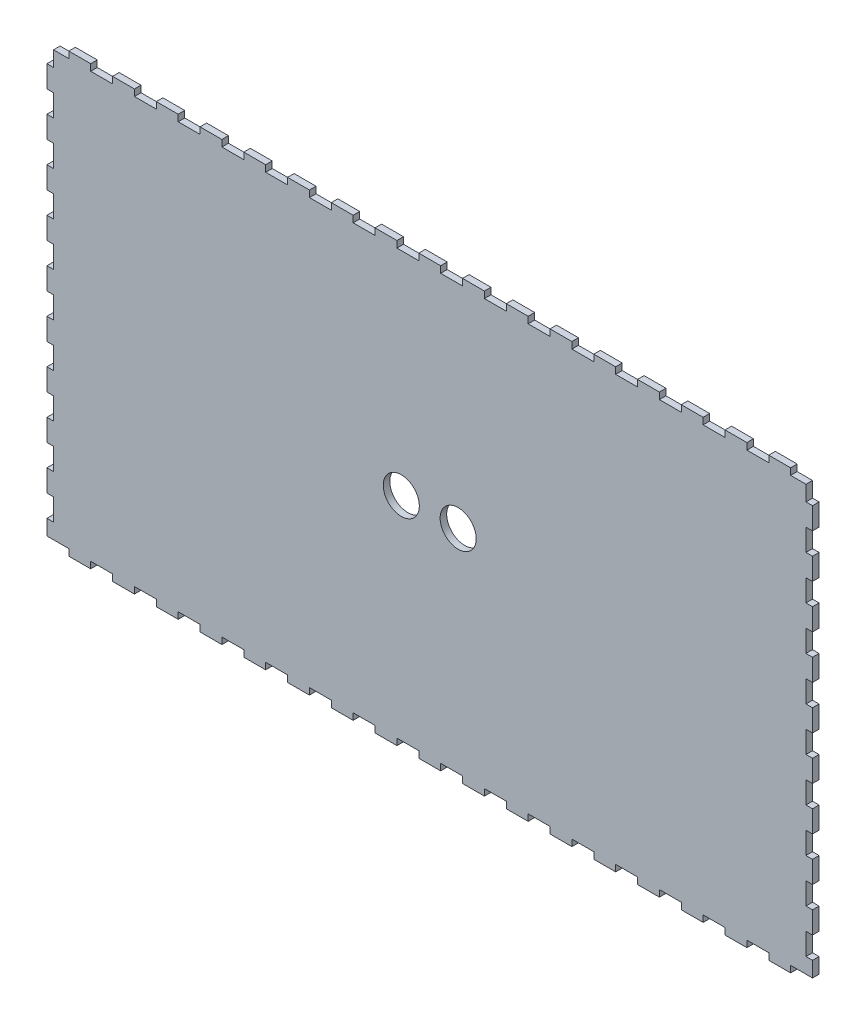
SolidWorks part; units mm, degrees
ref_plane "Alzado" through (0, 0, 0) normal (0, 0, 1) x (1, 0, 0)
ref_plane "Planta" through (0, 0, 0) normal (0, 1, 0) x (1, 0, 0)
ref_plane "Vista lateral" through (0, 0, 0) normal (1, 0, 0) x (0, 0, -1)
sketch "Croquis1" plane through (0, 0, 0) normal (0, 0, 1) x (1, 0, 0)
  line L0 (-175, -97) -> (-165, -97)
  line L1 (-155, -97) -> (-145, -97)
  line L3 (-175, 80) -> (-172, 80)
  line L4 (-172, 70) -> (-175, 70)
  line L5 (175, -100) -> (-175, 100) construction
  line L6 (175, 100) -> (-175, -100) construction
  line L103 (172, 97) -> (172, 90)
  line L105 (-172, 90) -> (-175, 90)
  line L106 (-175, 90) -> (-175, 80)
  line L107 (-175, 80) -> (-172, 80)
  line L108 (-175, 70) -> (-175, 60)
  line L109 (-175, 60) -> (-172, 60)
  line L110 (-172, 80) -> (-172, 70)
  line L111 (-175, 60) -> (-172, 60)
  line L112 (-172, 50) -> (-175, 50)
  line L113 (-175, 50) -> (-175, 40)
  line L114 (-175, 40) -> (-172, 40)
  line L115 (-172, 60) -> (-172, 50)
  line L116 (-175, 40) -> (-172, 40)
  line L117 (-172, 30) -> (-175, 30)
  line L118 (-175, 30) -> (-175, 20)
  line L119 (-175, 20) -> (-172, 20)
  line L120 (-172, 40) -> (-172, 30)
  line L121 (-175, 20) -> (-172, 20)
  line L122 (-172, 10) -> (-175, 10)
  line L123 (-175, 10) -> (-175, 0)
  line L124 (-175, 0) -> (-172, 0)
  line L125 (-172, 20) -> (-172, 10)
  line L126 (-175, 0) -> (-172, 0)
  line L127 (-172, -10) -> (-175, -10)
  line L128 (-175, -10) -> (-175, -20)
  line L129 (-175, -20) -> (-172, -20)
  line L130 (-172, 0) -> (-172, -10)
  line L131 (-175, -20) -> (-172, -20)
  line L132 (-172, -30) -> (-175, -30)
  line L133 (-175, -30) -> (-175, -40)
  line L134 (-175, -40) -> (-172, -40)
  line L135 (-172, -20) -> (-172, -30)
  line L136 (-175, -40) -> (-172, -40)
  line L137 (-172, -50) -> (-175, -50)
  line L138 (-175, -50) -> (-175, -60)
  line L139 (-175, -60) -> (-172, -60)
  line L140 (-172, -40) -> (-172, -50)
  line L141 (-175, -60) -> (-172, -60)
  line L142 (-172, -70) -> (-175, -70)
  line L143 (-175, -70) -> (-175, -80)
  line L144 (-175, -80) -> (-172, -80)
  line L145 (-172, -60) -> (-172, -70)
  line L146 (-175, -80) -> (-172, -80)
  line L147 (-172, -90) -> (-175, -90)
  line L148 (-175, -90) -> (-175, -97)
  line L149 (-145, -97) -> (-145, -100)
  line L150 (-172, -80) -> (-172, -90)
  line L151 (-33.9734, 0) -> (38.9566, 0) construction
  line L152 (172, -80) -> (172, -90)
  line L153 (165, 97) -> (172, 97)
  line L154 (175, -90) -> (175, -97)
  line L155 (172, -90) -> (175, -90)
  line L156 (175, -80) -> (172, -80)
  line L157 (172, -60) -> (172, -70)
  line L158 (175, -80) -> (172, -80)
  line L159 (175, -70) -> (175, -80)
  line L160 (172, -70) -> (175, -70)
  line L161 (175, -60) -> (172, -60)
  line L162 (172, -40) -> (172, -50)
  line L163 (175, -60) -> (172, -60)
  line L164 (175, -50) -> (175, -60)
  line L165 (172, -50) -> (175, -50)
  line L166 (175, -40) -> (172, -40)
  line L167 (172, -20) -> (172, -30)
  line L168 (175, -40) -> (172, -40)
  line L169 (175, -30) -> (175, -40)
  line L170 (172, -30) -> (175, -30)
  line L171 (175, -20) -> (172, -20)
  line L172 (172, 0) -> (172, -10)
  line L173 (175, -20) -> (172, -20)
  line L174 (175, -10) -> (175, -20)
  line L175 (172, -10) -> (175, -10)
  line L176 (175, 0) -> (172, 0)
  line L177 (172, 20) -> (172, 10)
  line L178 (175, 0) -> (172, 0)
  line L179 (175, 10) -> (175, 0)
  line L180 (172, 10) -> (175, 10)
  line L181 (175, 20) -> (172, 20)
  line L182 (172, 40) -> (172, 30)
  line L183 (175, 20) -> (172, 20)
  line L184 (175, 30) -> (175, 20)
  line L186 (172, 30) -> (175, 30)
  line L187 (175, 40) -> (172, 40)
  line L188 (172, 60) -> (172, 50)
  line L189 (175, 40) -> (172, 40)
  line L190 (175, 50) -> (175, 40)
  line L191 (172, 50) -> (175, 50)
  line L192 (175, 60) -> (172, 60)
  line L193 (172, 80) -> (172, 70)
  line L194 (175, 60) -> (172, 60)
  line L195 (175, 70) -> (175, 60)
  line L196 (175, 80) -> (172, 80)
  line L197 (175, 90) -> (175, 80)
  line L198 (172, 90) -> (175, 90)
  line L200 (172, 70) -> (175, 70)
  line L201 (175, 80) -> (172, 80)
  line L203 (-165, -97) -> (-165, -100)
  line L204 (-165, -100) -> (-155, -100)
  line L205 (-155, -100) -> (-155, -97)
  line L206 (-145, -100) -> (-135, -100)
  line L207 (-135, -100) -> (-135, -97)
  line L208 (-135, -97) -> (-125, -97)
  line L209 (-125, -97) -> (-125, -100)
  line L210 (-125, -100) -> (-115, -100)
  line L211 (-115, -100) -> (-115, -97)
  line L212 (-115, -97) -> (-105, -97)
  line L213 (-105, -97) -> (-105, -100)
  line L214 (-105, -100) -> (-95, -100)
  line L215 (-95, -100) -> (-95, -97)
  line L216 (-95, -97) -> (-85, -97)
  line L217 (-85, -97) -> (-85, -100)
  line L218 (-85, -100) -> (-75, -100)
  line L219 (-75, -100) -> (-75, -97)
  line L220 (-75, -97) -> (-65, -97)
  line L221 (-65, -97) -> (-65, -100)
  line L222 (-65, -100) -> (-55, -100)
  line L223 (-55, -100) -> (-55, -97)
  line L224 (-55, -97) -> (-45, -97)
  line L225 (-45, -97) -> (-45, -100)
  line L226 (-45, -100) -> (-35, -100)
  line L227 (-35, -100) -> (-35, -97)
  line L228 (-35, -97) -> (-25, -97)
  line L229 (-25, -97) -> (-25, -100)
  line L230 (-25, -100) -> (-15, -100)
  line L231 (-15, -100) -> (-15, -97)
  line L232 (-15, -97) -> (-5, -97)
  line L233 (-5, -97) -> (-5, -100)
  line L234 (-5, -100) -> (5, -100)
  line L235 (5, -100) -> (5, -97)
  line L236 (5, -97) -> (15, -97)
  line L237 (15, -97) -> (15, -100)
  line L238 (15, -100) -> (25, -100)
  line L239 (25, -100) -> (25, -97)
  line L240 (25, -97) -> (35, -97)
  line L241 (35, -97) -> (35, -100)
  line L242 (35, -100) -> (45, -100)
  line L243 (45, -100) -> (45, -97)
  line L244 (45, -97) -> (55, -97)
  line L245 (55, -97) -> (55, -100)
  line L246 (55, -100) -> (65, -100)
  line L247 (65, -100) -> (65, -97)
  line L248 (65, -97) -> (75, -97)
  line L249 (75, -97) -> (75, -100)
  line L250 (75, -100) -> (85, -100)
  line L251 (85, -100) -> (85, -97)
  line L255 (85, -97) -> (95, -97)
  line L256 (95, -97) -> (95, -100)
  line L257 (95, -100) -> (105, -100)
  line L258 (105, -100) -> (105, -97)
  line L259 (105, -97) -> (115, -97)
  line L260 (115, -97) -> (115, -100)
  line L261 (115, -100) -> (125, -100)
  line L262 (125, -100) -> (125, -97)
  line L263 (125, -97) -> (135, -97)
  line L264 (135, -97) -> (135, -100)
  line L265 (135, -100) -> (145, -100)
  line L266 (145, -100) -> (145, -97)
  line L267 (145, -97) -> (155, -97)
  line L268 (155, -97) -> (155, -100)
  line L269 (155, -100) -> (165, -100)
  line L270 (165, -100) -> (165, -97)
  line L271 (165, -97) -> (175, -97)
  line L272 (165, 100) -> (165, 97)
  line L273 (155, 100) -> (165, 100)
  line L274 (155, 97) -> (155, 100)
  line L275 (145, 97) -> (155, 97)
  line L276 (145, 100) -> (145, 97)
  line L277 (135, 100) -> (145, 100)
  line L278 (135, 97) -> (135, 100)
  line L279 (125, 97) -> (135, 97)
  line L280 (125, 100) -> (125, 97)
  line L281 (115, 100) -> (125, 100)
  line L282 (115, 97) -> (115, 100)
  line L283 (105, 97) -> (115, 97)
  line L284 (105, 100) -> (105, 97)
  line L285 (95, 100) -> (105, 100)
  line L286 (95, 97) -> (95, 100)
  line L287 (85, 97) -> (95, 97)
  line L288 (85, 100) -> (85, 97)
  line L289 (75, 100) -> (85, 100)
  line L290 (75, 97) -> (75, 100)
  line L291 (65, 97) -> (75, 97)
  line L292 (65, 100) -> (65, 97)
  line L293 (55, 100) -> (65, 100)
  line L294 (55, 97) -> (55, 100)
  line L295 (45, 97) -> (55, 97)
  line L296 (45, 100) -> (45, 97)
  line L297 (35, 100) -> (45, 100)
  line L298 (35, 97) -> (35, 100)
  line L299 (25, 97) -> (35, 97)
  line L300 (25, 100) -> (25, 97)
  line L301 (15, 100) -> (25, 100)
  line L302 (15, 97) -> (15, 100)
  line L303 (5, 97) -> (15, 97)
  line L304 (5, 100) -> (5, 97)
  line L305 (-5, 100) -> (5, 100)
  line L306 (-5, 97) -> (-5, 100)
  line L307 (-15, 97) -> (-5, 97)
  line L308 (-15, 100) -> (-15, 97)
  line L309 (-25, 100) -> (-15, 100)
  line L310 (-25, 97) -> (-25, 100)
  line L311 (-35, 97) -> (-25, 97)
  line L312 (-35, 100) -> (-35, 97)
  line L313 (-45, 100) -> (-35, 100)
  line L314 (-45, 97) -> (-45, 100)
  line L315 (-55, 97) -> (-45, 97)
  line L316 (-55, 100) -> (-55, 97)
  line L317 (-65, 100) -> (-55, 100)
  line L318 (-65, 97) -> (-65, 100)
  line L319 (-75, 97) -> (-65, 97)
  line L320 (-75, 100) -> (-75, 97)
  line L322 (-175, -100) -> (-172, -100) [skipped]
  line L323 (175, -100) -> (185, -100) [skipped]
  line L324 (185, -100) -> (185, -97) [skipped]
  line L325 (175, -97) -> (175, -100) [skipped]
  line L326 (-85, 100) -> (-75, 100)
  line L327 (-85, 97) -> (-85, 100)
  line L328 (-95, 97) -> (-85, 97)
  line L329 (-95, 100) -> (-95, 97)
  line L330 (-105, 100) -> (-95, 100)
  line L331 (-105, 97) -> (-105, 100)
  line L332 (-115, 97) -> (-105, 97)
  line L333 (-115, 100) -> (-115, 97)
  line L334 (-125, 100) -> (-115, 100)
  line L335 (-125, 97) -> (-125, 100)
  line L336 (-135, 97) -> (-125, 97)
  line L337 (-135, 100) -> (-135, 97)
  line L338 (-145, 100) -> (-135, 100)
  line L339 (-155, 100) -> (-155, 97)
  line L340 (-165, 100) -> (-155, 100)
  line L341 (-165, 97) -> (-165, 100)
  line L342 (-145, 97) -> (-145, 100)
  line L343 (-155, 97) -> (-145, 97)
  line L344 (-172, 97) -> (-165, 97)
  line L345 (-172, 97) -> (-172, 90)
  circle A0 centre (-13, 0) radius 8.25
  circle A1 centre (13, 0) radius 8.25
  point P0 (0, 0)
  point P1 (0, 0)
  point P148 (0, 0)
  dimension "D9" = 16.5
  dimension "D10" = 16.5
  dimension "D1" = 200
  dimension "D2" = 350
  dimension "D5" = 10
  dimension "D6" = 18
  dimension "D7" = 13
  dimension "D8" = 13
extrude "Saliente-Extruir1" add sketch "Croquis1" along normal blind 3 contours L344 L345 L105 L106 L3 L110 L4 L108 L109 L115 L112 L113 L114 L120 L117 L118 L119 L125 L122 L123 L124 L130 L127 L128 L129 L135 L132 L133 L134 L140 L137 L138 L139 L145 L142 L143 L144 L150 L147 L148 L0 L203 L204 L205 L1 L149 L206 L207 L208 L209 L210
